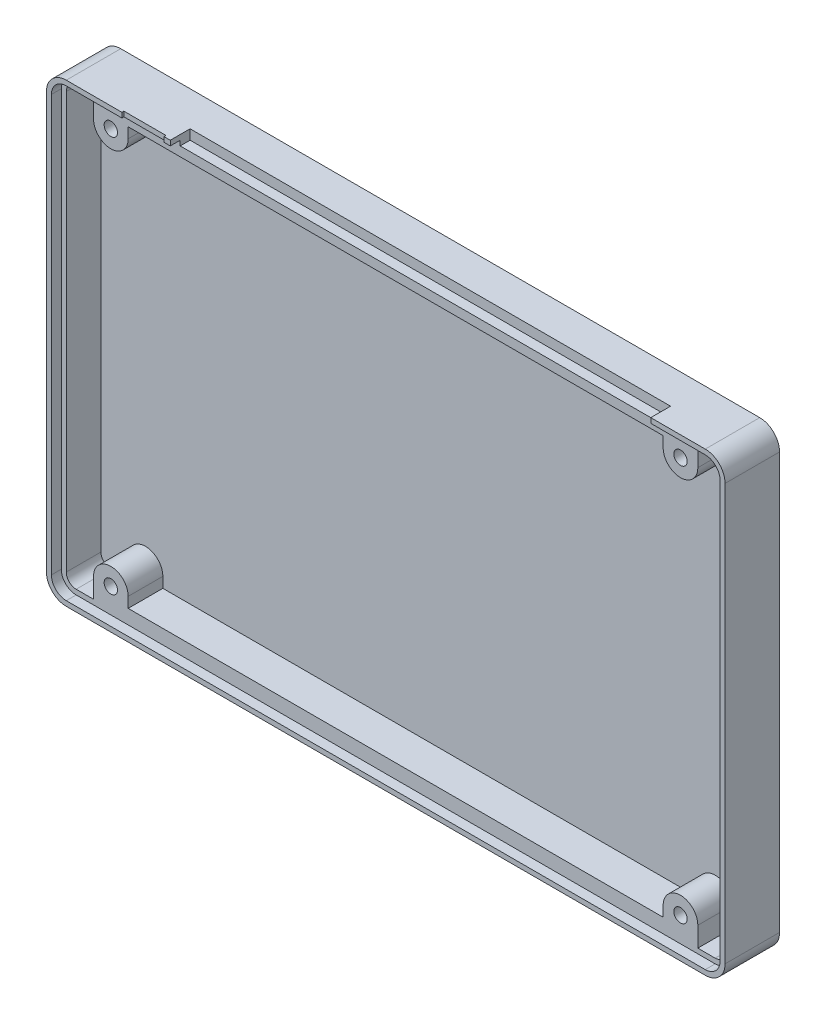
SolidWorks part; units mm, degrees
ref_plane "Front Plane" through (0, 0, 0) normal (0, 0, 1) x (1, 0, 0)
ref_plane "Top Plane" through (0, 0, 0) normal (0, 1, 0) x (1, 0, 0)
ref_plane "Right Plane" through (0, 0, 0) normal (1, 0, 0) x (0, 0, -1)
sketch "Sketch1" plane through (0, 0, 0) normal (0, 0, 1) x (1, 0, 0)
  line L1 (0, 0) -> (137, 0)
  line L2 (0, 0) -> (0, 92)
  line L3 (0, 92) -> (137, 92)
  line L4 (137, 0) -> (137, 92)
  dimension "D1" = 137
  dimension "D2" = 92
extrude "Boss-Extrude1" add sketch "Sketch1" along normal blind 2
sketch "Sketch2" plane through (0, 0, 2) normal (0, 0, 1) x (1, 0, 0)
  line L1 (0, 92) -> (137, 92)
  line L2 (0, 92) -> (0, 0)
  line L3 (0, 0) -> (137, 0)
  line L4 (137, 92) -> (137, 0)
  line L5 (2, 2) -> (135, 2)
  line L6 (2, 2) -> (2, 90)
  line L7 (2, 90) -> (135, 90)
  line L8 (135, 2) -> (135, 90)
  dimension "D1" = 2
  dimension "D2" = 2
  dimension "D3" = 2
  dimension "D4" = 2
extrude "Boss-Extrude2" add sketch "Sketch2" along normal blind 7
sketch "Sketch3" plane through (0, 0, 9) normal (0, 0, 1) x (1, 0, 0)
  line L1 (0, 0) -> (137, 0)
  line L2 (0, 0) -> (0, 92)
  line L3 (0, 92) -> (137, 92)
  line L4 (137, 0) -> (137, 92)
  line L5 (1, 1) -> (136, 1)
  line L6 (1, 1) -> (1, 91)
  line L7 (1, 91) -> (136, 91)
  line L8 (136, 1) -> (136, 91)
  dimension "D1" = 1
  dimension "D2" = 1
  dimension "D3" = 1
  dimension "D4" = 1
extrude "Boss-Extrude3" add sketch "Sketch3" along normal blind 2
sketch "Sketch4" plane through (0, 0, 2) normal (0, 0, 1) x (1, 0, 0)
  line L0 (0, 0) -> (137, 0) construction
  line L1 (0, 92) -> (0, 0) construction
  line L2 (2, 2) -> (135, 2) construction
  line L4 (7.5, 6) -> (7.5, 2)
  line L5 (7.5, 2) -> (14.5, 2)
  line L6 (14.5, 6) -> (14.5, 2)
  line L7 (137, 0) -> (137, 92) construction
  line L8 (137, 92) -> (0, 92) construction
  line L9 (2, 2) -> (135, 2) construction
  line L11 (122.5, 6) -> (122.5, 2)
  line L12 (122.5, 2) -> (129.5, 2)
  line L13 (129.5, 6) -> (129.5, 2)
  line L14 (135, 90) -> (2, 90) construction
  line L16 (129.5, 86) -> (129.5, 90)
  line L17 (129.5, 90) -> (122.5, 90)
  line L18 (122.5, 86) -> (122.5, 90)
  line L19 (135, 90) -> (2, 90) construction
  line L21 (14.5, 86) -> (14.5, 90)
  line L22 (14.5, 90) -> (7.5, 90)
  line L23 (7.5, 86) -> (7.5, 90)
  arc A0 (14.5, 6) -> (7.5, 6) centre (11, 6) ccw
  circle A1 centre (11, 6) radius 1.35
  arc A2 (7.5, 86) -> (14.5, 86) centre (11, 86) ccw
  circle A3 centre (11, 86) radius 1.35
  arc A4 (122.5, 86) -> (129.5, 86) centre (126, 86) ccw
  circle A5 centre (126, 86) radius 1.35
  arc A6 (129.5, 6) -> (122.5, 6) centre (126, 6) ccw
  circle A7 centre (126, 6) radius 1.35
  point P4 (0, 0)
  dimension "D1" = 2.7
  dimension "D2" = 7
  dimension "D3" = 2.7
  dimension "D4" = 7
  dimension "D5" = 2.7
  dimension "D6" = 7
  dimension "D7" = 2.7
  dimension "D8" = 7
  dimension "D11" = 6
  dimension "D9" = 6
  dimension "D10" = 11
  dimension "D12" = 11
  dimension "D13" = 11
  dimension "D14" = 6
  dimension "D15" = 11
  dimension "D16" = 6
extrude "Boss-Extrude4" add sketch "Sketch4" along normal blind 7
sketch "Sketch8" plane through (0, 0, 2) normal (0, 0, 1) x (1, 0, 0)
  line L0 (122.5, 6) -> (122.5, 2) construction
  line L1 (14.5, 2) -> (122.5, 2)
  line L2 (14.5, 2) -> (14.5, 3.9)
  line L3 (14.5, 3.9) -> (122.5, 3.9)
  line L4 (122.5, 2) -> (122.5, 3.9)
  dimension "D1" = 1.9
extrude "Boss-Extrude6" add sketch "Sketch8" along normal blind 7
fillet "Fillet1" radius 2 4 edges at (2, 2, 5.5) (135, 2, 5.5) (135, 90, 5.5) (2, 90, 5.5)
fillet "Fillet2" radius 3 4 edges at (1, 1, 10) (136, 1, 10) (136, 91, 10) (1, 91, 10)
fillet "Fillet3" radius 4 4 edges at (137, 92, 5.5) (0, 92, 5.5) (0, 0, 5.5) (137, 0, 5.5)
sketch "Sketch11" plane through (0, 0, 2) normal (0, 0, 1) x (1, 0, 0)
  line L0 (122.5, 90) -> (122.5, 86) construction
  line L1 (14.5, 90) -> (122.5, 90)
  line L2 (14.5, 90) -> (14.5, 88.1)
  line L3 (14.5, 88.1) -> (122.5, 88.1)
  line L4 (122.5, 90) -> (122.5, 88.1)
  dimension "D1" = 1.9
extrude "Boss-Extrude7" add sketch "Sketch11" along normal blind 7
sketch "Sketch12" plane through (0, 92, 0) normal (0, 1, 0) x (1, 0, 0)
  line L0 (133, -11) -> (4, -11) construction
  line L1 (25, -11) -> (122, -11)
  line L2 (25, -11) -> (25, -7)
  line L3 (25, -7) -> (122, -7)
  line L4 (122, -11) -> (122, -7)
  line L5 (0, -11) -> (0, 0) construction
  dimension "D1" = 4
  dimension "D2" = 97
  dimension "D3" = 25
extrude "Cut-Extrude3" cut sketch "Sketch12" against normal blind 2
sketch "Sketch13" plane through (0, 0, 9) normal (0, 0, 1) x (1, 0, 0)
  circle A0 centre (11, 86) radius 1.35
  circle A1 centre (11, 6) radius 1.35
  circle A2 centre (126, 6) radius 1.35
  circle A3 centre (126, 86) radius 1.35
  dimension "D1" = 2.7
  dimension "D2" = 2.7
  dimension "D3" = 2.7
  dimension "D4" = 2.7
extrude "Cut-Extrude4" cut sketch "Sketch13" against normal blind 10
sketch "Sketch14" plane through (0, 92, 0) normal (0, 1, 0) x (1, 0, 0)
  line L0 (25, -11) -> (4, -11) construction
  line L1 (15.2382, -11) -> (23.7382, -11)
  line L2 (15.2382, -11) -> (15.2382, -10.6)
  line L3 (15.2382, -10.6) -> (23.7382, -10.6)
  line L4 (23.7382, -11) -> (23.7382, -10.6)
  dimension "D1" = 8.5
  dimension "D2" = 0.4
extrude "Cut-Extrude5" cut sketch "Sketch14" against normal blind 2
sketch "Sketch16" plane through (0, 0, 0) normal (0, 0, -1) x (-1, 0, 0)
  circle A0 centre (-126, 86) radius 3
  circle A1 centre (-11, 86) radius 3
  circle A2 centre (-11, 6) radius 3
  circle A3 centre (-126, 6) radius 3
extrude "Cut-Extrude12" cut sketch "Sketch16" against normal blind 2
